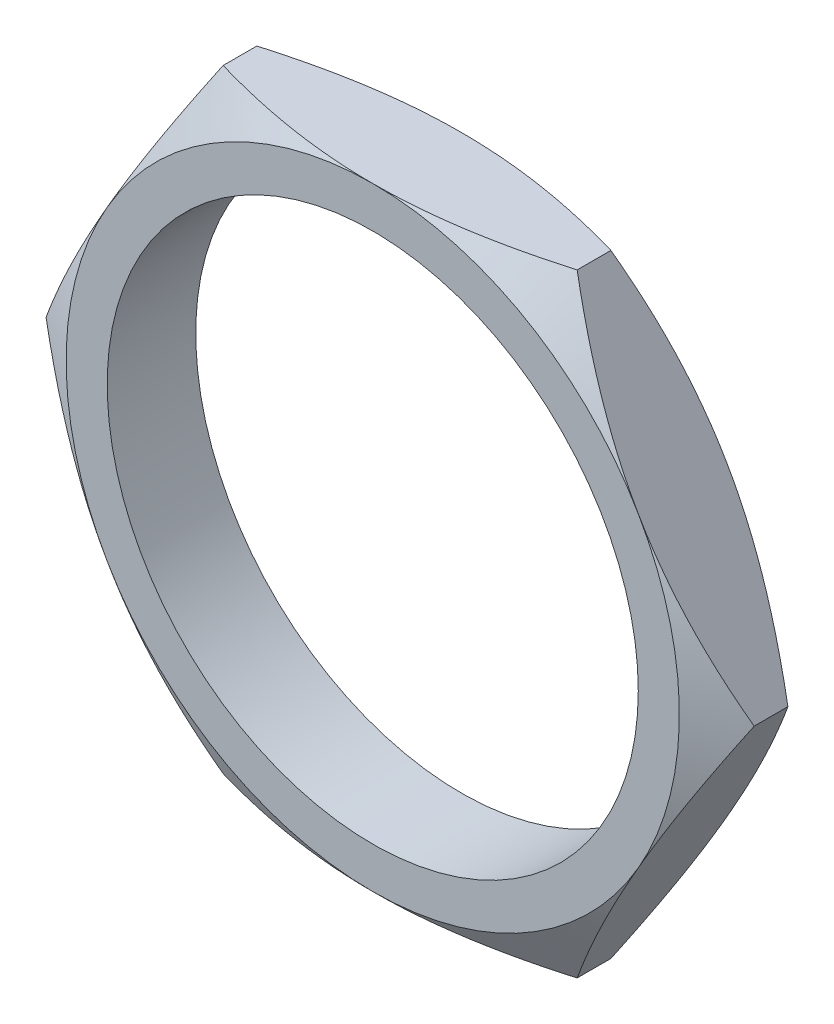
SolidWorks part; units mm, degrees
ref_plane "Płaszczyzna przednia" through (0, 0, 0) normal (0, 0, 1) x (1, 0, 0)
ref_plane "Płaszczyzna górna" through (0, 0, 0) normal (0, 1, 0) x (1, 0, 0)
ref_plane "Płaszczyzna prawa" through (0, 0, 0) normal (1, 0, 0) x (0, 0, -1)
sketch "Szkic1" plane through (0, 0, 0) normal (0, 0, 1) x (1, 0, 0)
  line L1 (10, 17.3205) -> (-10, 17.3205)
  line L2 (-10, 17.3205) -> (-20, 0)
  line L3 (-20, 0) -> (-10, -17.3205)
  line L4 (-10, -17.3205) -> (10, -17.3205)
  line L5 (10, -17.3205) -> (20, 0)
  line L6 (20, 0) -> (10, 17.3205)
  circle A0 centre (0, 0) radius 17.3205 construction
  dimension "D1" = 40
extrude "Dodanie-wyciągnięcie1" add sketch "Szkic1" along normal blind 5
sketch "Szkic2" plane through (0, 0, 0) normal (0, 0, 1) x (1, 0, 0)
  line L0 (-10, 17.3205) -> (-20, 0) construction
  circle A0 centre (0, 0) radius 17.3205
extrude "Wytnij-wyciągnięcie1" cut sketch "Szkic2" along normal blind 25 draft 60 flip side to cut contours A0
sketch "Szkic3" plane through (0, 0, 0) normal (0, 0, 1) x (1, 0, 0)
  circle A0 centre (0, 0) radius 15
  dimension "D1" = 30
extrude "Wytnij-wyciągnięcie5" cut sketch "Szkic3" along normal blind 15
ref_plane "Płaszczyzna1" through (0, 0, 5) normal (0, 0, 1) x (1, 0, 0)
sketch "Szkic5" plane through (0, 0, 5) normal (0, 0, 1) x (1, 0, 0)
  line L0 (-10, 17.3205) -> (-20, 0) construction
  circle A0 centre (0, 0) radius 17.3205
extrude "Wytnij-wyciągnięcie8" cut sketch "Szkic5" against normal blind 10 draft 60 flip side to cut
equation "\"D1@Szkic3\" = 30"
equation "\"D1@Szkic1\"= 40"
